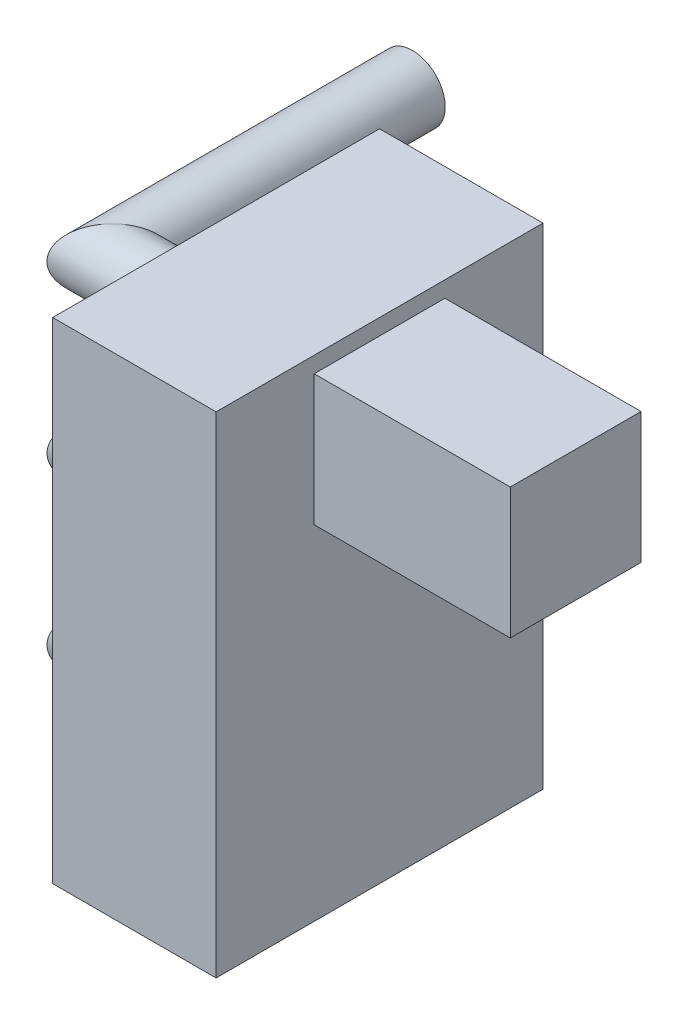
SolidWorks part; units mm, degrees
ref_plane "前视基准面" through (0, 0, 0) normal (0, 0, 1) x (1, 0, 0)
ref_plane "上视基准面" through (0, 0, 0) normal (0, 1, 0) x (1, 0, 0)
ref_plane "右视基准面" through (0, 0, 0) normal (1, 0, 0) x (0, 0, -1)
sketch "草图1" plane through (0, 0, 0) normal (0, 0, 1) x (1, 0, 0)
  line L0 (2.5, -6.285) -> (2.5, -13.785)
  line L1 (0, -6.285) -> (2.5, -6.285)
  line L2 (0, -6.285) -> (0, -13.785)
  line L3 (0, -13.785) -> (2.5, -13.785)
  dimension "D1" = 7.5
extrude "凸台-拉伸1" add sketch "草图1" along normal blind 5
sketch "草图2" plane through (2.5, 0, 0) normal (1, 0, 0) x (0, 0, -1)
  line L0 (-2.5, -6.285) -> (-2.5, -13.785) construction
  line L1 (-5, -6.285) -> (0, -6.285) construction
  line L2 (-5, -13.785) -> (0, -13.785) construction
  line L3 (-3.5, -6.5305) -> (-1.5, -6.5305)
  line L4 (-1.5, -6.5305) -> (-1.5, -8.5305)
  line L5 (-1.5, -8.5305) -> (-3.5, -8.5305)
  line L6 (-3.5, -6.5305) -> (-3.5, -8.5305)
  point P11 (-2.5, -8.5305)
  point P12 (-2.5, -6.5305)
  dimension "D1" = 2
  dimension "D2" = 2
extrude "凸台-拉伸2" add sketch "草图2" along normal blind 3
sketch "草图3" plane through (0, 0, 0) normal (-1, 0, 0) x (0, 0, 1)
  line L0 (2.5921, -6.285) -> (2.5921, -13.785) construction
  line L1 (5, -6.285) -> (0, -6.285) construction
  line L2 (5, -13.785) -> (0, -13.785) construction
  line L3 (0, -10.035) -> (5, -10.035) construction
  line L4 (0, -6.285) -> (0, -13.785) construction
  line L5 (5, -6.285) -> (5, -13.785) construction
  circle A0 centre (2.5921, -10.035) radius 0.5
  circle A1 centre (2.5921, -7.495) radius 0.5
  circle A2 centre (2.5921, -12.575) radius 0.5
  dimension "D1" = 1
  dimension "D2" = 1
  dimension "D3" = 2.54
ref_plane "基准面1" through (0, -10.035, 0) normal (0, -1, 0) x (1, 0, 0)
sketch "草图4" plane through (0, -10.035, 0) normal (0, -1, 0) x (1, 0, 0)
  line L0 (0, 3.097) -> (-2, 3.097)
  line L1 (0, 0) -> (0, 5) construction
  line L2 (-2, 3.097) -> (-2, -2)
  dimension "D1" = 2
sweep "扫描1" add profiles "草图3" path "草图4"
